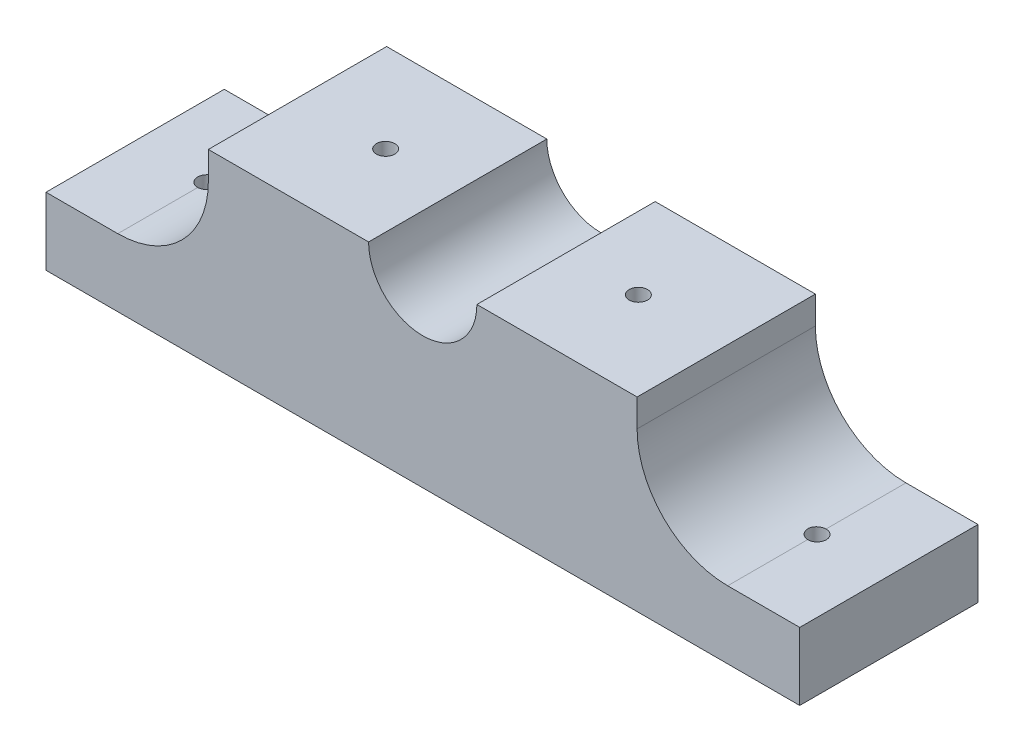
SolidWorks part; units mm, degrees
material "Custom Plastic"
ref_plane "Front Plane" through (0, 0, 0) normal (0, 0, 1) x (1, 0, 0)
ref_plane "Top Plane" through (0, 0, 0) normal (0, 1, 0) x (1, 0, 0)
ref_plane "Right Plane" through (0, 0, 0) normal (1, 0, 0) x (0, 0, -1)
sketch "Sketch2" plane through (0, 0, 0) normal (0, 1, 0) x (1, 0, 0)
  line L1 (-20.873, -4.9365) -> (20.873, -4.9365)
  line L2 (-20.873, -4.9365) -> (-20.873, 4.9365)
  line L3 (-20.873, 4.9365) -> (20.873, 4.9365)
  line L4 (20.873, -4.9365) -> (20.873, 4.9365)
  line L5 (-20.873, -4.9365) -> (20.873, 4.9365) construction
  line L6 (-20.873, 4.9365) -> (20.873, -4.9365) construction
  point P0 (0, 0)
  dimension "D1" = 41.746
  dimension "D2" = 9.873
extrude "Boss-Extrude1" add sketch "Sketch2" along normal blind 3.746 contours L1 L4 L3 L2
sketch "Sketch3" plane through (0, 3.746, 0) normal (0, 1, 0) x (1, 0, 0)
  line L0 (-11.8803, 4.9365) -> (-11.8803, -4.9365)
  line L1 (-20.873, 4.9365) -> (20.873, 4.9365) construction
  line L2 (-11.8803, 4.9365) -> (11.8657, 4.9365)
  line L3 (-20.873, -4.9365) -> (20.873, -4.9365) construction
  line L4 (-11.8803, -4.9365) -> (11.8657, -4.9365)
  line L5 (11.8657, -4.9365) -> (11.8657, 4.9365)
extrude "Boss-Extrude2" add sketch "Sketch3" along normal blind 6.5485
fillet "Fillet1" radius 5.0165 2 edges at (11.8657, 3.746, 0) (-11.8803, 3.746, 0)
sketch "Sketch4" plane through (0, 0, 4.9365) normal (0, 0, 1) x (1, 0, 0)
  line L0 (-11.8803, 10.2945) -> (11.8657, 10.2945) construction
  circle A0 centre (-0.0073, 10.2945) radius 2.9997
extrude "Cut-Extrude1" cut sketch "Sketch4" against normal through all
sketch "Sketch5" plane through (0, 10.2945, 0) normal (0, 1, 0) x (1, 0, 0)
  line L0 (-11.8803, 4.9365) -> (11.8657, 4.9365)
  line L1 (11.8657, 4.9365) -> (11.8657, -4.9365)
  line L2 (11.8657, -4.9365) -> (-11.8803, -4.9365)
  line L3 (-16.8968, -4.9365) -> (-11.8803, -4.9365) construction
  line L4 (-11.8803, -4.9365) -> (-3.0071, -4.9365) construction
  line L5 (-11.8803, -4.9365) -> (-11.8803, 4.9365)
sketch "Sketch6" plane through (0, 3.746, 0) normal (0, 1, 0) x (1, 0, 0)
  line L2 (-16.8968, -4.9365) -> (-16.8968, 4.9365) construction
  circle A0 centre (-16.8968, 0) radius 0.508
  circle A1 centre (16.8968, 0) radius 0.508
  point P0 (0, 0)
extrude "Cut-Extrude2" cut sketch "Sketch6" against normal blind 2.54 and the other way through all
sketch "Sketch7" plane through (0, 10.2945, 0) normal (0, 1, 0) x (1, 0, 0)
  circle A0 centre (-7, 0) radius 0.508
  circle A1 centre (7, 0) radius 0.508
  point P2 (0, 0)
  point P4 (0, 0)
  point P7 (0, 0)
extrude "Cut-Extrude3" cut sketch "Sketch7" against normal blind 2.54
